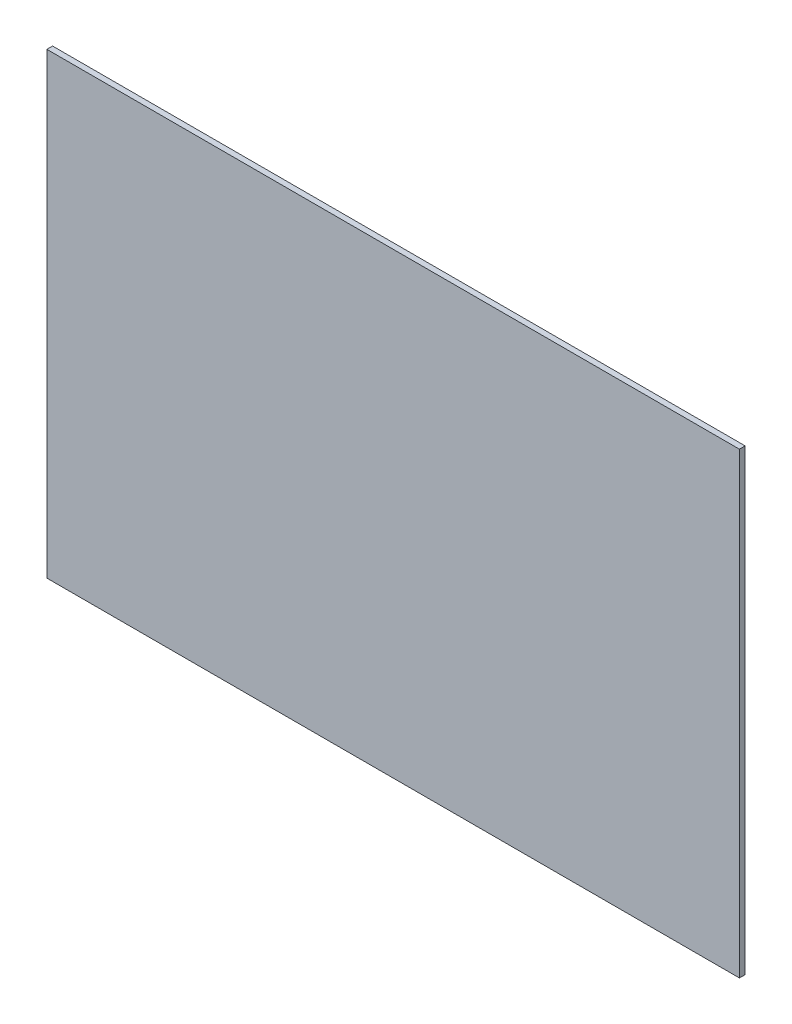
SolidWorks part; units mm, degrees
material "AISI 4340 Steel, annealed"
ref_plane "Front Plane" through (0, 0, 0) normal (0, 0, 1) x (1, 0, 0)
ref_plane "Top Plane" through (0, 0, 0) normal (0, 1, 0) x (1, 0, 0)
ref_plane "Right Plane" through (0, 0, 0) normal (1, 0, 0) x (0, 0, -1)
sketch "Sketch1" plane through (0, 0, 0) normal (0, 0, 1) x (1, 0, 0)
  line L1 (-302.475, 200) -> (302.475, 200)
  line L2 (-302.475, 200) -> (-302.475, -200)
  line L3 (-302.475, -200) -> (302.475, -200)
  line L4 (302.475, 200) -> (302.475, -200)
  line L5 (-302.475, 200) -> (302.475, -200) construction
  line L6 (-302.475, -200) -> (302.475, 200) construction
  point P0 (0, 0)
  dimension "D1" = 400
  dimension "D2" = 604.95
extrude "Boss-Extrude1" add sketch "Sketch1" along normal blind 5
